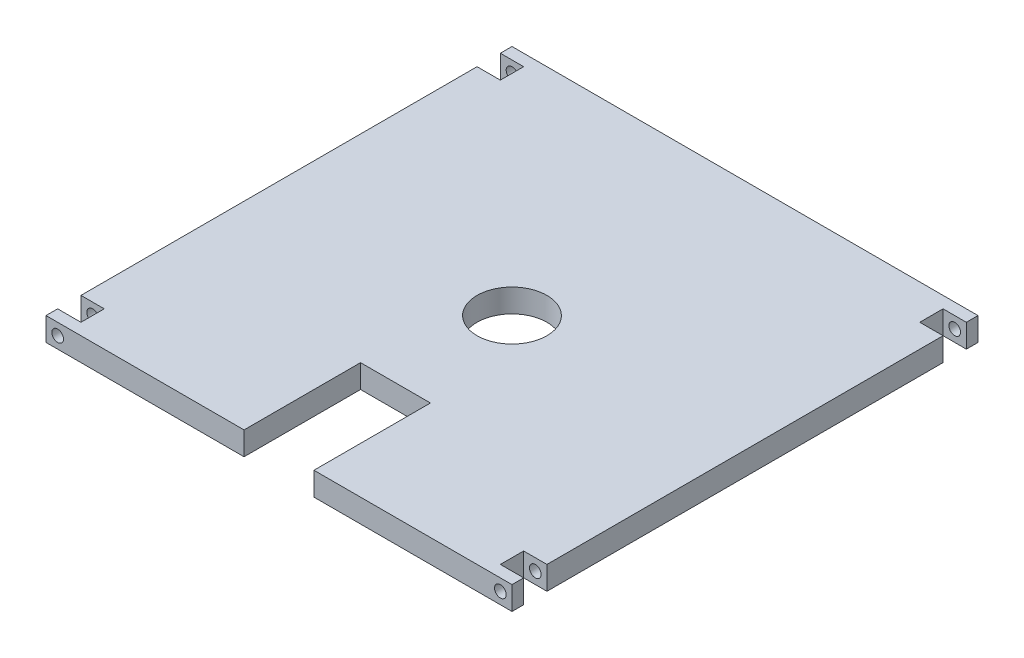
SolidWorks part; units mm, degrees
ref_plane "Plan de face" through (0, 0, 0) normal (0, 0, 1) x (1, 0, 0)
ref_plane "Plan de dessus" through (0, 0, 0) normal (0, 1, 0) x (1, 0, 0)
ref_plane "Plan de droite" through (0, 0, 0) normal (1, 0, 0) x (0, 0, -1)
sketch "Esquisse1" plane through (0, 0, 0) normal (0, 1, 0) x (1, 0, 0)
  line L0 (-100, 95) -> (-90, 95)
  line L1 (100, 100) -> (-100, 100)
  line L2 (100, 100) -> (100, 95)
  line L3 (100, -100) -> (15, -100)
  line L4 (-100, 100) -> (-100, 95)
  line L5 (100, 100) -> (-100, -100) construction
  line L6 (100, -100) -> (-100, 100) construction
  line L7 (-90, 95) -> (-90, 85)
  line L8 (-90, 85) -> (-100, 85)
  line L9 (-100, 85) -> (-100, -85)
  line L10 (46.6264, 0) -> (-32.5251, 0) construction
  line L11 (-90, -95) -> (-90, -85)
  line L12 (-100, -95) -> (-90, -95)
  line L13 (-90, -85) -> (-100, -85)
  line L14 (0, 41.9741) -> (0, -29.1916) construction
  line L15 (100, -95) -> (90, -95)
  line L16 (90, -95) -> (90, -85)
  line L17 (90, -85) -> (100, -85)
  line L18 (90, 95) -> (90, 85)
  line L19 (100, 95) -> (90, 95)
  line L20 (90, 85) -> (100, 85)
  line L21 (-100, -95) -> (-100, -100)
  line L22 (100, -95) -> (100, -100)
  line L23 (100, 85) -> (100, -85)
  line L24 (0, 0) -> (0, -148.2919) construction
  line L25 (-15, -100) -> (-100, -100)
  line L27 (-15, -100) -> (-15, -50)
  line L28 (-15, -50) -> (15, -50)
  line L29 (15, -100) -> (15, -50)
  line L30 (-21.7851, -169.808) -> (15, -50) construction
  line L31 (-15, -50) -> (21.4513, -168.7209) construction
  circle A0 centre (0, 0) radius 15
  point P0 (0, 0)
  point P6 (-100, 95)
  point P29 (0, -98.8545)
  dimension "D6" = 30
  dimension "D1" = 200
  dimension "D2" = 200
  dimension "D3" = 5
  dimension "D4" = 10
  dimension "D5" = 10
  dimension "D7" = 120
  dimension "D8" = 30
  dimension "D9" = 50
extrude "BASE" add sketch "Esquisse1" along normal blind 10
sketch "Esquisse2" plane through (0, 0, 100) normal (0, 0, 1) x (1, 0, 0)
  line L0 (-100, 5) -> (100, 5) construction
  line L1 (-100, 10) -> (-100, 0) construction
  line L2 (100, 10) -> (100, 0) construction
  line L3 (0, 17.8445) -> (0, -8.2411) construction
  circle A0 centre (-95, 5) radius 2.5
  circle A1 centre (95, 5) radius 2.5
  dimension "D1" = 5
  dimension "D2" = 5
extrude "Enlèv. mat.-Extru.1" cut sketch "Esquisse2" against normal through all
